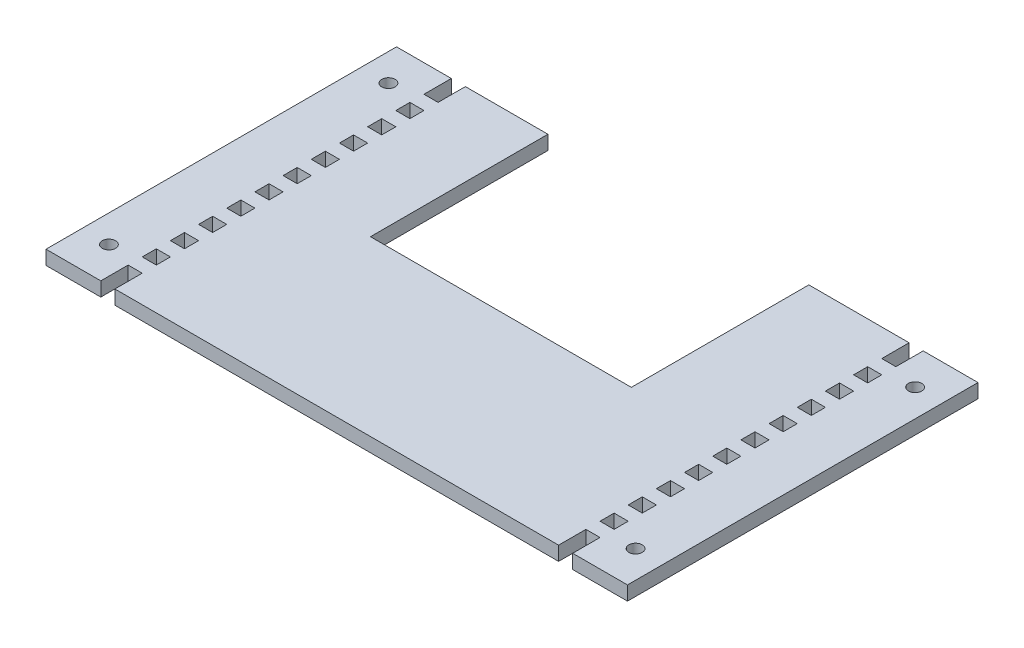
SolidWorks part; units mm, degrees
ref_plane "Front Plane" through (0, 0, 0) normal (0, 0, 1) x (1, 0, 0)
ref_plane "Top Plane" through (0, 0, 0) normal (0, 1, 0) x (1, 0, 0)
ref_plane "Right Plane" through (0, 0, 0) normal (1, 0, 0) x (0, 0, -1)
sketch "Sketch2" plane through (0, 0, 0) normal (0, 1, 0) x (1, 0, 0)
  line L1 (-4, -17) -> (96, -17) construction
  line L2 (-4, -17) -> (-4, 62) construction
  line L3 (-4, 62) -> (96, 62) construction
  line L4 (96, -17) -> (96, 62) construction
  circle A0 centre (0, 0) radius 1.38 construction
  circle A1 centre (0, 58) radius 1.38 construction
  circle A2 centre (86, 58) radius 1.38 construction
  circle A3 centre (86, 0) radius 1.38 construction
  dimension "D5" = 2.76
  dimension "D1" = 100
  dimension "D2" = 79
  dimension "D3" = 4
  dimension "D4" = 17
  dimension "D6" = 4
  dimension "D7" = 4
  dimension "D8" = 4
  dimension "D9" = 10
  dimension "D10" = 10
  dimension "D11" = 17
sketch "Sketch3" plane through (0, 0, 0) normal (0, 1, 0) x (1, 0, 0)
  line L1 (-4, 62) -> (96, 62)
  line L2 (-4, 62) -> (-4, -17)
  line L3 (-4, -17) -> (96, -17)
  line L4 (96, 62) -> (96, -17)
extrude "Boss-Extrude1" add sketch "Sketch3" along normal blind 3.175
sketch "Sketch4" plane through (0, 3.175, 0) normal (0, 1, 0) x (1, 0, 0)
  circle A0 centre (0, 58) radius 1.38
  circle A1 centre (86, 58) radius 1.38
  circle A2 centre (86, 0) radius 1.38
  circle A3 centre (0, 0) radius 1.38
  dimension "D1" = 2.76
extrude "Cut-Extrude1" [suppressed] cut sketch "Sketch4" against normal blind 3.175
sketch "Sketch5" plane through (0, 3.175, 0) normal (0, 1, 0) x (1, 0, 0)
  line L0 (-4, 62) -> (96, 62) construction
  line L1 (14.6, 62) -> (73.4, 62)
  line L2 (14.6, 62) -> (14.6, 22)
  line L3 (14.6, 22) -> (73.4, 22)
  line L4 (73.4, 62) -> (73.4, 22)
  dimension "D1" = 14.6
  dimension "D2" = 40
  dimension "D3" = 58.8
extrude "Cut-Extrude2" cut sketch "Sketch5" against normal blind 3.175
sketch "Sketch8" plane through (96, 0, 0) normal (1, 0, 0) x (0, 0, -1)
  line L1 (-17, 3.175) -> (62, 3.175)
  line L2 (-17, 3.175) -> (-17, 0)
  line L3 (-17, 0) -> (62, 0)
  line L4 (62, 3.175) -> (62, 0)
sketch "Sketch9" plane through (-4, 0, 0) normal (-1, 0, 0) x (0, 0, 1)
  line L0 (17, 0) -> (-62, 0) construction
  line L1 (-62, 3.175) -> (17, 3.175)
  line L2 (-62, 3.175) -> (-62, 0)
  line L3 (-62, 0) -> (17, 0)
  line L4 (17, 3.175) -> (17, 0)
ref_plane "Plane3" through (46, 0, 0) normal (-1, 0, 0) x (0, 0, 1)
ref_plane "Plane4" through (0, 0, -22.5) normal (0, 0, -1) x (-1, 0, 0)
sketch "Sketch11" plane through (0, 3.175, 0) normal (0, 1, 0) x (1, 0, 0)
  line L0 (-4, -17) -> (-4, 62) construction
  line L1 (-0.825, 20.9125) -> (-7.175, 20.9125)
  line L2 (-0.825, 20.9125) -> (-0.825, 24.0875)
  line L3 (-0.825, 24.0875) -> (-7.175, 24.0875)
  line L4 (-7.175, 20.9125) -> (-7.175, 24.0875)
  line L5 (-0.825, 20.9125) -> (-7.175, 24.0875) construction
  line L6 (-0.825, 24.0875) -> (-7.175, 20.9125) construction
  point P0 (-4, 22.5)
  dimension "D1" = 6.35
  dimension "D2" = 3.175
extrude "Boss-Extrude2" add sketch "Sketch11" against normal up to surface (3.175 mm away) up to face at (45, 0, -32.25)
mirror "Mirror2" about plane through (46, 0, 0) normal (-1, 0, 0) of "Boss-Extrude2"
pattern_linear "LPattern2" count 6 spacing 6.35 along (0, 0, -1) count 6 spacing 6.35 along (0, 0, 1) of "Mirror2", "Boss-Extrude2"
sketch "Sketch12" plane through (0, 3.175, 0) normal (0, 1, 0) x (1, 0, 0)
  circle A0 centre (0, 58) radius 3
  circle A1 centre (0, 0) radius 3
  circle A2 centre (86, 58) radius 3
  circle A3 centre (86, 0) radius 3
  dimension "D1" = 6
extrude "Cut-Extrude3" [suppressed] cut sketch "Sketch12" against normal up to next
sketch "Sketch13" plane through (0, 3.175, 0) normal (0, 1, 0) x (1, 0, 0)
  line L1 (-7.175, 62) -> (-19.525, 62)
  line L2 (-7.175, 62) -> (-7.175, -17)
  line L3 (-7.175, -17) -> (-19.525, -17)
  line L4 (-19.525, 62) -> (-19.525, -17)
  line L6 (-7.175, 30.4375) -> (-7.175, 27.2625) construction
  dimension "D1" = 12.35
extrude "Boss-Extrude4" add sketch "Sketch13" against normal up to surface (3.175 mm away) up to face at (45.9167, 0, -23.3125)
sketch "Sketch14" plane through (0, 3.175, 0) normal (0, 1, 0) x (1, 0, 0)
  line L1 (99.175, 62) -> (111.525, 62)
  line L2 (99.175, 62) -> (99.175, -17)
  line L3 (99.175, -17) -> (111.525, -17)
  line L4 (111.525, 62) -> (111.525, -17)
  dimension "D1" = 12.35
extrude "Boss-Extrude5" add sketch "Sketch14" against normal up to surface (3.175 mm away) up to face at (-5.5875, 0, -25.675)
sketch "Sketch15" plane through (0, 3.175, 0) normal (0, 1, 0) x (1, 0, 0)
  line L0 (-13.35, 73.46) -> (-13.35, -30.7789) construction
  line L1 (-19.525, 62) -> (-19.525, -17) construction
  line L2 (-7.175, 62) -> (-19.525, 62) construction
  circle A0 centre (-13.35, 54) radius 1.5
  circle A1 centre (-13.35, -9) radius 1.5
  dimension "D2" = 3
  dimension "D3" = 3
  dimension "D1" = 6.175
  dimension "D4" = 63
  dimension "D5" = 8
sketch "Sketch16" plane through (0, 3.175, 0) normal (0, 1, 0) x (1, 0, 0)
  line L0 (105.35, 68.5201) -> (105.35, 28.0125) construction
  line L1 (111.525, -17) -> (111.525, 62) construction
  line L2 (111.525, 62) -> (99.175, 62) construction
  line L3 (99.175, -17) -> (111.525, -17) construction
  circle A0 centre (105.35, 54) radius 1.5
  circle A1 centre (105.35, -9) radius 1.5
  dimension "D4" = 3
  dimension "D5" = 3
  dimension "D1" = 6.175
  dimension "D2" = 8
  dimension "D3" = 8
extrude "Cut-Extrude4" cut sketch "Sketch15" against normal blind 10
extrude "Cut-Extrude5" cut sketch "Sketch16" against normal blind 10
